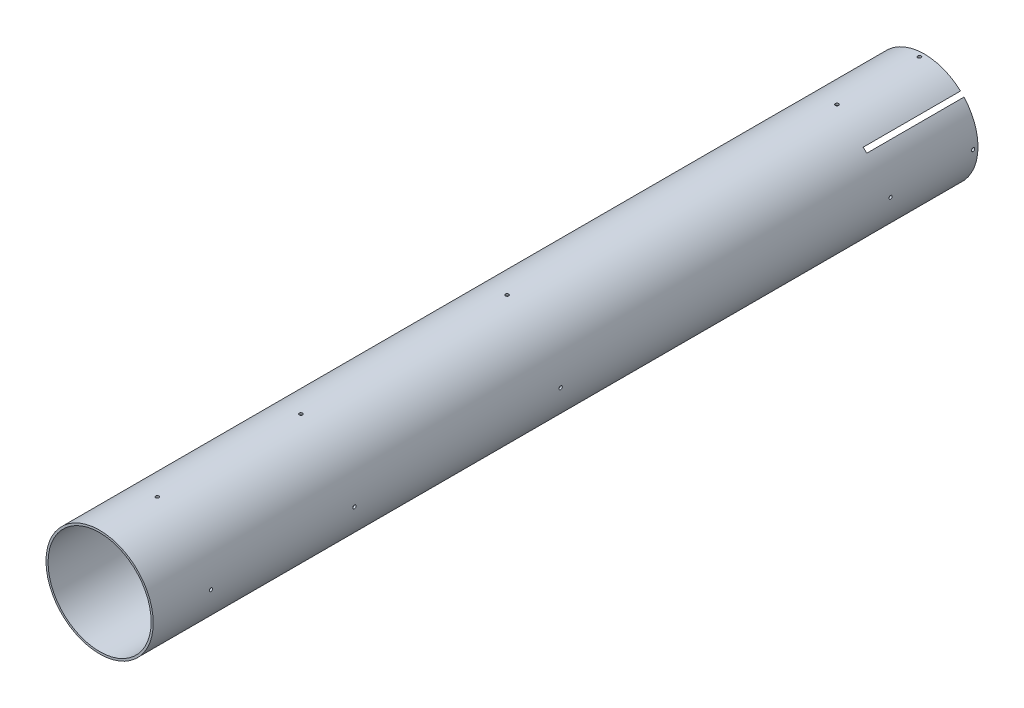
SolidWorks part; units mm, degrees
material "E-Glass Fiber"
ref_plane "Ön Düzlem" through (0, 0, 0) normal (0, 0, 1) x (1, 0, 0)
ref_plane "Üst Düzlem" through (0, 0, 0) normal (0, 1, 0) x (1, 0, 0)
ref_plane "Sağ Düzlem" through (0, 0, 0) normal (1, 0, 0) x (0, 0, -1)
sketch "Sketch1" plane through (0, 0, 0) normal (0, 0, 1) x (1, 0, 0)
  circle A0 centre (0, 0) radius 65
  circle A1 centre (0, 0) radius 62.5
  dimension "D1" = 130
  dimension "D2" = 2.5
extrude "Boss-Extrude1" add sketch "Sketch1" along normal mid plane 1000
sketch "Sketch3" plane through (0, 0, 0) normal (0, 1, 0) x (1, 0, 0)
  line L0 (0, 500) -> (0, 494) construction
  line L1 (65, 500) -> (-65, 500) construction
  line L2 (0, 494) -> (0, 394) construction
  line L3 (0, 394) -> (0, -6) construction
  line L4 (0, -6) -> (0, -256) construction
  line L5 (0, -256) -> (0, -430) construction
  line L6 (0, -430) -> (0, -500) construction
  line L7 (-65, -500) -> (65, -500) construction
  circle A0 centre (0, 494) radius 2
  circle A1 centre (0, 394) radius 2
  circle A2 centre (0, -6) radius 2
  circle A3 centre (0, -256) radius 2
  circle A4 centre (0, -430) radius 2
  dimension "D6" = 4
  dimension "D1" = 70
  dimension "D2" = 244
  dimension "D3" = 494
  dimension "D4" = 894
  dimension "D5" = 994
extrude "Cut-Extrude2" cut sketch "Sketch3" against normal mid plane 280
sketch "Sketch4" plane through (0, 0, 0) normal (1, 0, 0) x (0, 0, -1)
  line L0 (-500, 0) -> (-430, 0) construction
  line L1 (-500, 65) -> (-500, -65) construction
  line L2 (-430, 0) -> (-256, 0) construction
  line L3 (-256, 0) -> (-6, 0) construction
  line L4 (-6, 0) -> (394, 0) construction
  line L5 (394, 0) -> (494, 0) construction
  line L6 (494, 0) -> (500, 0) construction
  line L7 (500, -65) -> (500, 65) construction
  circle A0 centre (-430, 0) radius 2
  circle A1 centre (-256, 0) radius 2
  circle A2 centre (-6, 0) radius 2
  circle A3 centre (394, 0) radius 2
  circle A4 centre (494, 0) radius 2
  dimension "D7" = 4
  dimension "D1" = 70
  dimension "D2" = 244
  dimension "D3" = 494
  dimension "D4" = 894
  dimension "D5" = 994
  dimension "D6" = 1000
extrude "Cut-Extrude3" cut sketch "Sketch4" against normal mid plane 589
sketch "Sketch2" plane through (0, 0, -500) normal (0, 0, -1) x (-1, 0, 0)
  line L0 (0, 0) -> (65, 0) construction
  line L1 (0, 0) -> (45.9619, 45.9619) construction
  line L2 (43.7916, 48.0343) -> (42.0219, 46.2646)
  line L3 (48.0343, 43.7916) -> (46.2646, 42.0219)
  circle A3 centre (0, 0) radius 65
  circle A4 centre (0, 0) radius 62.5
  circle M19 centre (0, 0) radius 65
  circle M20 centre (0, 0) radius 62.5
  dimension "D2" = 130
  dimension "D4" = 3
  dimension "D5" = 3
  dimension "D1" = 45
  dimension "D3" = 125
extrude "Cut-Extrude4" cut sketch "Sketch2" against normal blind 118 contours L3 L2 M19 M20
pattern_circular "CirPattern1" count 4 over 360 about axis through (0, 0, 0) along (0, 0, 1) of "Cut-Extrude4"
